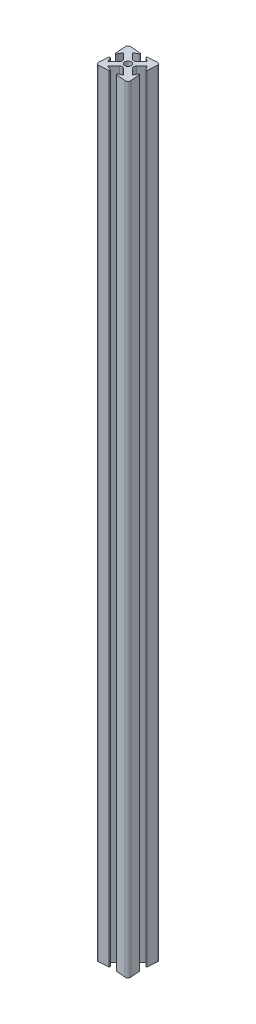
SolidWorks part; units mm, degrees
ref_plane "Front Plane" through (0, 0, 0) normal (0, 0, 1) x (1, 0, 0)
ref_plane "Top Plane" through (0, 0, 0) normal (0, 1, 0) x (1, 0, 0)
ref_plane "Right Plane" through (0, 0, 0) normal (1, 0, 0) x (0, 0, -1)
sketch "Sketch1" plane through (0, 0, 0) normal (0, 1, 0) x (1, 0, 0)
  line L1 (-16.2586, 10.8064) -> (9.1414, 10.8064)
  line L2 (-16.2586, 10.8064) -> (-16.2586, -14.5936)
  line L3 (-16.2586, -14.5936) -> (9.1414, -14.5936)
  line L4 (9.1414, 10.8064) -> (9.1414, -14.5936)
  dimension "D1" = 25.4
  dimension "D2" = 25.4
sketch "Sketch2" plane through (0, 0, 0) normal (0, 1, 0) x (1, 0, 0)
  line L0 (-19.5248, -1.8936) -> (12.956, -1.8936)
  line L1 (-3.2844, -16.3317) -> (-3.2844, 12.7118)
  line L2 (-16.2586, -14.5936) -> (9.1414, 10.8064)
  line L3 (-16.2586, 10.8064) -> (9.1414, -14.5936)
  line L4 (-16.2586, -14.5936) -> (-15.2113, -2.9758)
  line L5 (-15.2113, -2.9758) -> (-12.9014, -8.3163)
  line L6 (-12.9014, -8.3163) -> (2.3702, 7.1647)
  line L8 (-1.9815, 9.9398) -> (9.1414, 10.8064)
  line L9 (-16.2586, -14.5936) -> (-4.6409, -13.5463)
  line L10 (-4.6409, -13.5463) -> (-9.9814, -11.2364)
  line L11 (-9.9814, -11.2364) -> (5.4997, 4.0353)
  line L12 (5.4997, 4.0353) -> (8.2747, -0.3164)
  line L13 (8.2747, -0.3164) -> (9.1414, 10.8064)
  line L14 (-15.392, -0.9626) -> (-12.6169, 3.7508)
  line L15 (-12.6169, 3.7508) -> (2.3702, -11.2364)
  line L16 (-15.392, -0.9626) -> (-16.2586, 10.8064)
  line L17 (2.3702, -11.2364) -> (-2.3468, -13.5463)
  line L18 (-2.3468, -13.5463) -> (9.1414, -14.5936)
  line L19 (5.7842, -7.8224) -> (8.0941, -3.1054)
  line L20 (-4.4895, 9.9398) -> (-9.203, 7.1647)
  line L21 (-9.203, 7.1647) -> (5.7842, -7.8224)
  line L22 (-4.4895, 9.9398) -> (-16.2586, 10.8064)
  line L23 (8.0941, -3.1054) -> (9.1414, -14.5936)
  line L24 (2.3702, 7.1647) -> (-1.9815, 9.9398)
extrude "Boss-Extrude1" add sketch "Sketch2" along normal blind 603.25 contours L20 L22 L3 L6 L21 | L16 L14 L15 L6 L3 | L2 L21 L0 L11 L12 L13 | L1 L21 L2 L8 L24 L6 | L15 L0 L6 L5 L4 L2 | L6 L15 L0 L3 | L21 L6 L3 L2 L1 | L0 L15 L2 | L2 L15 L11 L1 L3 | L21 L0 L1 L3 L11 | L21 L1 L2 | L21 L2 L1 L0 | L6 L21 L1 | L1 L11 L3 | L0 L21 L11 | L15 L6 L0 | L2 L0 L1 | L0 L3 L1 | L23 L19 L21 L11 L3 | L17 L18 L3 L11 L1 L15 | L15 L2 L9 L10 L11
sketch "Sketch8" plane through (0, 603.25, 0) normal (0, 1, 0) x (1, 0, 0)
  circle A0 centre (-3.527, -1.9152) radius 2.5653
extrude "Cut-Extrude4" cut sketch "Sketch8" against normal blind 604.996
fillet "Fillet1" radius 2.032 4 edges at (9.1414, 301.625, 14.5936) (-16.2586, 301.625, 14.5936) (9.1414, 301.625, -10.8064) (-16.2586, 301.625, -10.8064)
fillet "Fillet2" radius 0.508 8 edges at (8.0941, 301.625, 3.1054) (-2.3468, 301.625, 13.5463) (-4.6409, 301.625, 13.5463) (-15.392, 301.625, 0.9626) (-15.2113, 301.625, 2.9758) (-4.4895, 301.625, -9.9398) (-1.9815, 301.625, -9.9398) (8.2747, 301.625, 0.3164)
sketch "Sketch5" plane through (-0.7818, 0, -10.0333) normal (-0.0777, 0, -0.997) x (-0.997, 0, 0.0777)
  line L1 (-3.8674, 570.4548) -> (8.7883, 570.4548)
  line L2 (-3.8674, 570.4548) -> (-3.8674, 294.9774)
  line L3 (-3.8674, 294.9774) -> (8.7883, 294.9774)
  line L4 (8.7883, 570.4548) -> (8.7883, 294.9774)
extrude "Boss-Extrude3" add sketch "Sketch5" along normal blind 4.572 contours L2 L1 L4 L3
sketch "Sketch6" plane through (-1.1369, 0, -14.5914) normal (-0.0777, 0, -0.997) x (-0.997, 0, 0.0777)
  line L0 (2.4604, 570.4548) -> (2.4604, 387.4972)
  line L1 (-3.8674, 570.4548) -> (8.7883, 570.4548) construction
  circle A0 centre (2.4604, 545.2326) radius 4.6177
  circle A1 centre (2.4604, 513.8542) radius 4.5036
  circle A2 centre (2.4604, 479.2551) radius 4.6219
  circle A3 centre (2.4604, 446.3016) radius 4.6727
  circle A4 centre (2.4604, 414.3422) radius 4.616
extrude "Cut-Extrude2" cut sketch "Sketch6" against normal blind 4.572 contours A4 | A3 | A2 | A1 | A0
sketch "Sketch7" plane through (-1.1369, 0, -14.5914) normal (-0.0777, 0, -0.997) x (-0.997, 0, 0.0777)
  circle A0 centre (2.6102, 377.3779) radius 4.5449
  circle A1 centre (2.1574, 338.1358) radius 4.6727
extrude "Cut-Extrude3" cut sketch "Sketch7" against normal blind 4.572 contours A1 | A0
fillet "Fillet3" radius 2.286 4 edges at (-0.3263, 301.625, 1.7119) (-3.377, 301.625, -1.3387) (-6.7677, 301.625, 2.0985) (-3.7635, 301.625, 5.1026)
